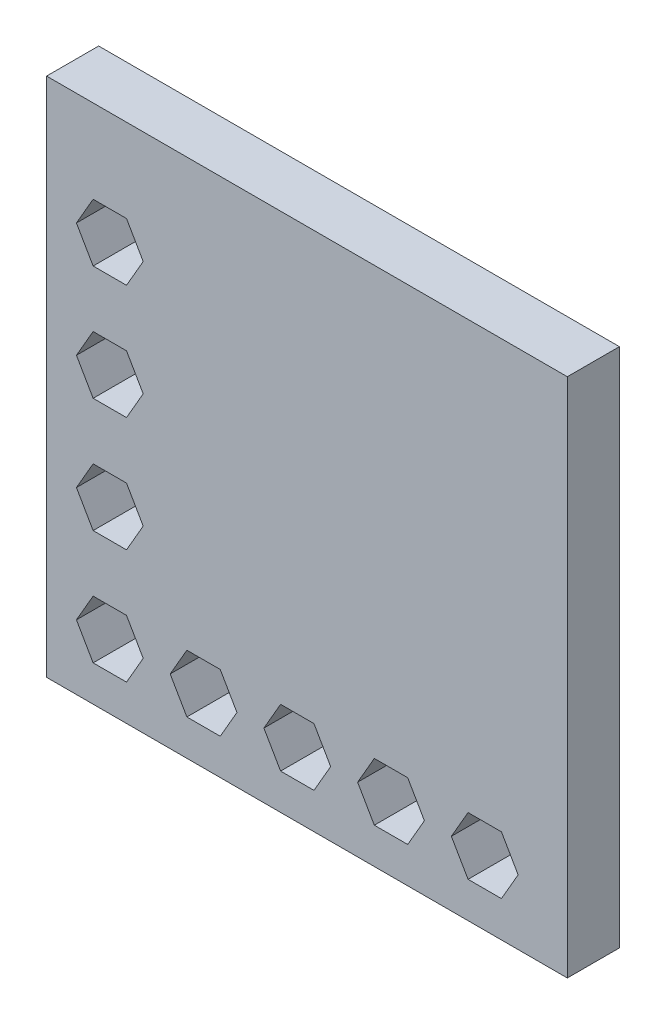
SolidWorks part; units mm, degrees
ref_plane "前基準面" through (0, 0, 0) normal (0, 0, 1) x (1, 0, 0)
ref_plane "上基準面" through (0, 0, 0) normal (0, 1, 0) x (1, 0, 0)
ref_plane "右基準面" through (0, 0, 0) normal (1, 0, 0) x (0, 0, -1)
sketch "草圖1" plane through (0, 0, 0) normal (0, 0, 1) x (1, 0, 0)
  line L1 (0, 0) -> (100, 0)
  line L2 (0, 0) -> (0, 100)
  line L3 (0, 100) -> (100, 100)
  line L4 (100, 0) -> (100, 100)
  dimension "D1" = 100
extrude "伸長1" add sketch "草圖1" along normal blind 10
sketch "草圖2" plane through (0, 0, 10) normal (0, 0, 1) x (1, 0, 0)
  line L1 (15.3464, 17.9835) -> (8.9354, 17.9835)
  line L2 (8.9354, 17.9835) -> (5.7299, 12.4314)
  line L3 (5.7299, 12.4314) -> (8.9354, 6.8793)
  line L4 (8.9354, 6.8793) -> (15.3464, 6.8793)
  line L5 (15.3464, 6.8793) -> (18.552, 12.4314)
  line L6 (18.552, 12.4314) -> (15.3464, 17.9835)
  circle A0 centre (12.1409, 12.4314) radius 5.5521 construction
extrude "伸長2" cut sketch "草圖2" against normal through all
pattern_linear "直線複製排列1" count 4 spacing 22 along (0, 1, 0) count 5 spacing 18 along (1, 0, 0) of "伸長2"
